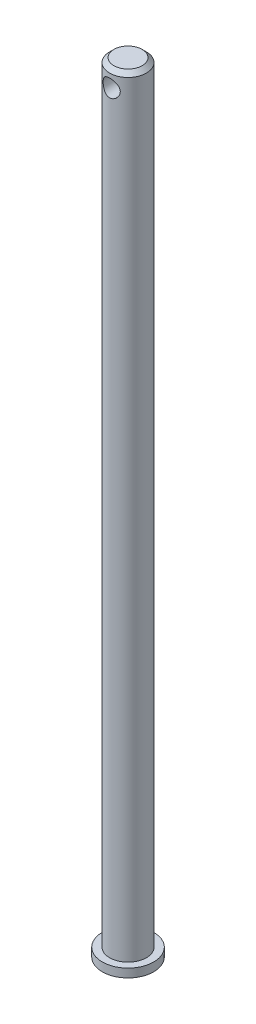
SolidWorks part; units mm, degrees
ref_plane "Front Plane" through (0, 0, 0) normal (0, 0, 1) x (1, 0, 0)
ref_plane "Top Plane" through (0, 0, 0) normal (0, 1, 0) x (1, 0, 0)
ref_plane "Right Plane" through (0, 0, 0) normal (1, 0, 0) x (0, 0, -1)
sketch "Sketch1" plane through (0, 0, 0) normal (0, 1, 0) x (1, 0, 0)
  circle A0 centre (0, 0) radius 2.15
  dimension "D1" = 4.3
extrude "Boss-Extrude1" add sketch "Sketch1" along normal blind 90
chamfer "Chamfer1" distance 0.5 angle 45 1 edges at (0, 90, 2.15)
sketch "Sketch2" plane through (0, 0, 0) normal (0, -1, 0) x (-1, 0, 0)
  circle A0 centre (0, 0) radius 3
  dimension "D1" = 6
extrude "Boss-Extrude2" add sketch "Sketch2" along normal blind 1
sketch "Sketch3" plane through (0, 0, 0) normal (0, 0, 1) x (1, 0, 0)
  line L0 (0, 90) -> (0, 79.4278) construction
  line L1 (1.65, 90) -> (-1.65, 90) construction
  circle A0 centre (0, 88) radius 1
  dimension "D1" = 2
  dimension "D2" = 2
extrude "Cut-Extrude1" cut sketch "Sketch3" against normal through all both and the other way through all
